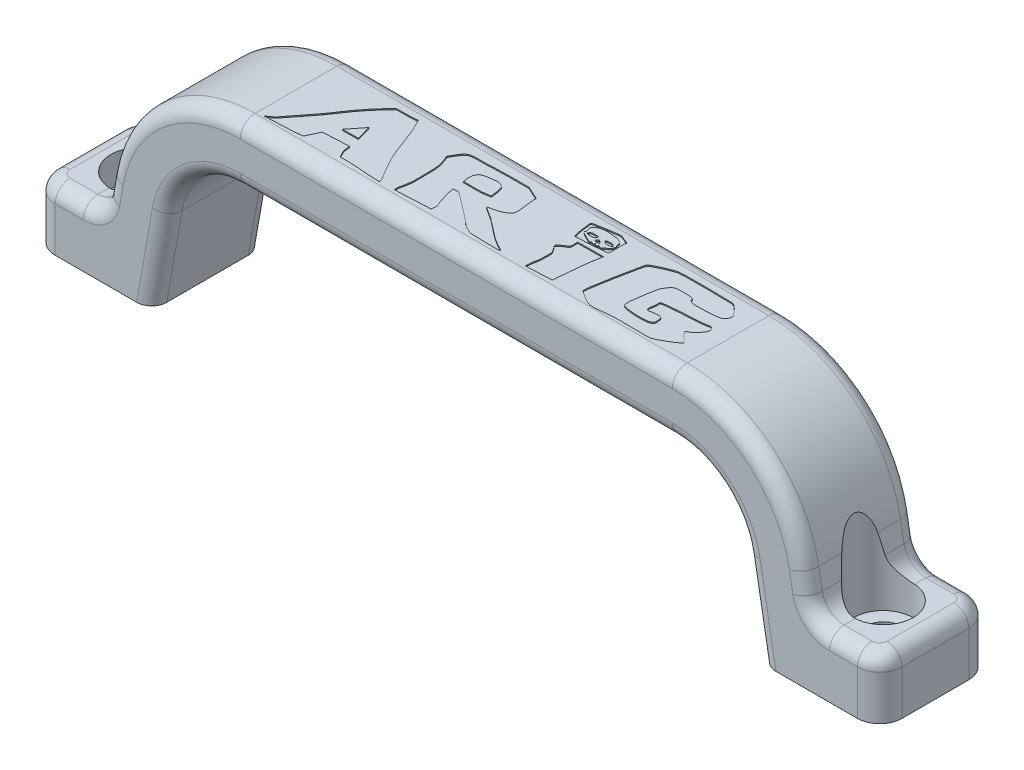
SolidWorks part; units mm, degrees
material "ABS"
ref_plane "Plan de face" through (0, 0, 0) normal (0, 0, 1) x (1, 0, 0)
ref_plane "Plan de dessus" through (0, 0, 0) normal (0, 1, 0) x (1, 0, 0)
ref_plane "Plan de droite" through (0, 0, 0) normal (1, 0, 0) x (0, 0, -1)
sketch "Esquisse1" plane through (0, 0, 0) normal (0, 0, 1) x (1, 0, 0)
  line L0 (-57, 0) -> (-41, 0)
  line L1 (-41, 0) -> (-38.9305, 11.7365)
  line L2 (-29.0825, 20) -> (29.0825, 20)
  line L3 (0, 20) -> (0, 0) construction
  line L4 (41, 0) -> (38.9305, 11.7365)
  line L5 (57, 0) -> (41, 0)
  arc A0 (38.9305, 11.7365) -> (29.0825, 20) centre (29.0825, 10) ccw
  arc A1 (-38.9305, 11.7365) -> (-29.0825, 20) centre (-29.0825, 10) cw
  dimension "D1" = 10
  dimension "D2" = 16
  dimension "D3" = 80
  dimension "D4" = 20
  dimension "D5" = 82
  dimension "D6" = 114
extrude "Extru.-Mince1" add sketch "Esquisse1" along normal mid plane 15 thin thin type one direction wall 8
fillet "Congé1" radius 3 6 edges at (57, 4, -7.5) (57, 4, 7.5) (-57, 4, -7.5) (-57, 4, 7.5) (47.7128, 8, 0) (-47.7128, 8, 0)
fillet "Congé2" radius 2 34 edges at (39.9653, 5.8682, -7.5) (35.5103, 17.6604, -7.5) (0, 20, -7.5) (-35.5103, 17.6604, -7.5) (39.9653, 5.8682, 7.5) (35.5103, 17.6604, 7.5) (0, 20, 7.5) (-35.5103, 17.6604, 7.5) (-56.1213, 8, 6.6213) (-52.115, 8, 7.5) (-48.3017, 8.7019, 7.5) (-47.0423, 11.8024, 7.5) (-40.6526, 23.7888, 7.5) (0, 28, 7.5) (40.6526, 23.7888, 7.5) (47.0423, 11.8024, 7.5) (48.3017, 8.7019, 7.5) (52.115, 8, 7.5) (56.1213, 8, 6.6213) (57, 8, 0) (56.1213, 8, -6.6213) (52.115, 8, -7.5) (48.3017, 8.7019, -7.5) (47.0423, 11.8024, -7.5) (40.6526, 23.7888, -7.5) (0, 28, -7.5) (-40.6526, 23.7888, -7.5) (-47.0423, 11.8024, -7.5) (-48.3017, 8.7019, -7.5) (-52.115, 8, -7.5) (-56.1213, 8, -6.6213) (-39.9653, 5.8682, -7.5) (-39.9653, 5.8682, 7.5) (-57, 8, 0)
hole_wizard "Chambrage pour vis à tête cylindrique à 6 pans creux (ou vis CHC) M41" positions "Esquisse3" profile "Esquisse4" counterbore size "M4" standard "Ansi Metric" end condition through all
sketch "Esquisse3" plane through (0, 8, 0) normal (0, 1, 0) x (1, 0, 0)
  line L0 (0, 0) -> (0, -7.5) construction
  line L1 (29.0825, -7.5) -> (-29.0825, -7.5) construction
  line L3 (-57, -4.5) -> (-57, 4.5) construction
  point P0 (-50, 0)
  point P2 (50, 0)
  dimension "D1" = 7
  dimension "D2" = 100
sketch "Esquisse4" plane through (-50, 8, 0) normal (1, 0, 0) x (0, 0, 1)
  line L0 (0, 0) -> (0, 8)
  line L1 (0, 8) -> (2.15, 8)
  line L2 (0, 0) -> (0, -20)
  line L3 (2.15, 8) -> (2.15, 4)
  line L4 (2.15, 4) -> (4, 4)
  line L5 (4, 4) -> (4, 0)
  line L6 (0, -20) -> (4, -20)
  line L7 (4, 0) -> (0, 0) construction
  line L8 (4, -20) -> (4, 0)
  line L11 (0, -6.35) -> (0, 107.95) construction
  dimension "Diamètre du perçage jusqu'au prochain" = 4.3
  dimension "Profondeur du perçage jusqu'au prochain" = 8
  dimension "Diamètre du chambrage" = 8
  dimension "Profondeur du chambrage" = 4
sketch "Esquisse5" plane through (0, 28, 0) normal (0, 1, 0) x (1, 0, 0)
  line L0 (-29.0825, -5.5) -> (29.0825, -5.5) construction
  line L1 (-29.0825, -5.5) -> (29.0825, -5.5) construction
  line L2 (-18.889, -2.9854) -> (-22.3764, -3.1611)
  line L3 (-20.7574, 3.9425) -> (-20.1614, 4.5686)
  line L4 (-21.3417, -1.4652) -> (-19.2272, -1.4434)
  line L5 (-2.0037, 4.3142) -> (-0.2156, 3.4955)
  line L6 (7.6307, 1.2068) -> (11.0963, 1.2403)
  line L7 (10.3429, -4.9341) -> (6.8672, -5.1049)
  line L8 (8.3288, 2.0373) -> (8.4745, 2.0373)
  line L9 (8.4745, 2.0373) -> (8.5314, 2.1963)
  line L10 (8.5314, 2.1963) -> (8.7457, 2.0322)
  line L11 (8.7457, 2.0322) -> (9.0035, 2.0373)
  line L12 (9.0035, 2.0373) -> (8.9583, 2.2298)
  line L13 (8.9583, 2.2298) -> (9.2396, 2.049)
  line L14 (9.2396, 2.049) -> (9.4539, 2.0607)
  line L15 (9.4539, 2.0607) -> (9.3869, 2.2532)
  line L16 (9.3869, 2.2532) -> (9.7569, 2.0657)
  line L17 (9.7569, 2.0657) -> (9.993, 2.1277)
  line L18 (9.2848, 2.5127) -> (8.8913, 2.4391)
  spline S0 degree 3 poles (-14.4356, -1.9792) (-14.0607, -2.6907) (-13.6011, -3.4612) (-13.0938, -4.2959) (-12.9746, -4.5033) (-12.8804, -4.6792) (-12.8098, -4.8224) (-12.7662, -4.9366) (-12.7443, -5.0296) (-12.7525, -5.0965) (-12.7932, -5.0982) knots 0 0 0 0 0.673145 0.751125 0.817898 0.873508 0.91803 0.951887 0.974709 1 1 1 1
  spline S1 degree 3 poles (-12.7932, -5.0982) (-12.8467, -5.1028) (-12.9417, -5.1016) (-13.0874, -5.1004) (-13.2403, -5.0944) (-13.4227, -5.0879) (-13.6349, -5.0798) (-13.8765, -5.0679) (-14.1387, -5.0526) (-14.4056, -5.0391) (-14.6595, -5.0218) (-14.8927, -5.0052) (-15.1048, -4.9887) (-15.2962, -4.9717) (-15.5098, -4.9518) (-15.6591, -4.9312) (-15.7515, -4.9174) knots 0 0 0 0 0.054223 0.096001 0.147401 0.208975 0.280725 0.362112 0.453705 0.546426 0.632419 0.71109 0.783006 0.847609 0.905466 1 1 1 1
  spline S2 degree 3 poles (-15.7515, -4.9174) (-15.8417, -4.9054) (-15.9856, -4.891) (-16.189, -4.8765) (-16.367, -4.8661) (-16.5629, -4.8595) (-16.7762, -4.8574) (-17.0066, -4.8527) (-17.2455, -4.854) (-17.4771, -4.8539) (-17.6847, -4.853) (-17.8605, -4.8559) (-18.0045, -4.8553) (-18.1166, -4.8554) (-18.202, -4.8554) (-18.25, -4.8554) (-18.2712, -4.8554) knots 0 0 0 0 0.108138 0.172034 0.242512 0.320224 0.405204 0.496157 0.594402 0.689329 0.771642 0.841347 0.898435 0.942911 0.974775 1 1 1 1
  spline S3 degree 3 poles (-18.2712, -4.8554) (-18.278, -4.8446) (-18.2906, -4.8196) (-18.3144, -4.776) (-18.3465, -4.7195) (-18.3862, -4.6453) (-18.4365, -4.5558) (-18.4953, -4.4499) (-18.5821, -4.2927) (-18.6816, -4.0971) (-18.7917, -3.8172) (-18.8281, -3.6105) (-18.822, -3.4826) knots 0 0 0 0 0.025534 0.05606 0.09962 0.155674 0.224762 0.305364 0.39846 0.58452 0.744873 1 1 1 1
  spline S4 degree 3 poles (-18.822, -3.4826) (-18.821, -3.4173) (-18.8438, -3.2512) (-18.867, -3.0856) (-18.889, -2.9854) knots 0 0 0 0 0.388377 1 1 1 1
  spline S5 degree 3 poles (-22.3764, -3.1611) (-22.5656, -3.5495) (-22.776, -3.9803) (-22.9897, -4.455) (-23.042, -4.5667) (-23.085, -4.6618) (-23.1209, -4.7399) (-23.148, -4.8005) (-23.1708, -4.8461) (-23.182, -4.872) (-23.1867, -4.8839) knots 0 0 0 0 0.680866 0.755243 0.82016 0.875251 0.919717 0.955522 0.979907 1 1 1 1
  spline S6 degree 3 poles (-23.1867, -4.8839) (-23.1989, -4.8862) (-23.2275, -4.8891) (-23.2777, -4.8963) (-23.3439, -4.9071) (-23.4284, -4.9177) (-23.532, -4.9341) (-23.6545, -4.9494) (-23.8404, -4.9773) (-24.0796, -5.0077) (-24.4485, -5.0391) (-24.7194, -5.0547) (-24.896, -5.053) knots 0 0 0 0 0.021624 0.050129 0.088552 0.138678 0.198718 0.271429 0.354053 0.526763 0.691971 1 1 1 1
  spline S7 degree 3 poles (-24.896, -5.053) (-24.9993, -5.0541) (-25.1684, -5.0559) (-25.4128, -5.0652) (-25.6389, -5.0728) (-25.8927, -5.0854) (-26.1752, -5.0982) (-26.4854, -5.1155) (-26.8124, -5.1332) (-27.1311, -5.1506) (-27.4179, -5.1679) (-27.6601, -5.1813) (-27.8583, -5.1912) (-28.0123, -5.199) (-28.13, -5.2073) (-28.1965, -5.2094) (-28.226, -5.212) knots 0 0 0 0 0.092911 0.1522 0.220037 0.296445 0.380903 0.474438 0.576024 0.675603 0.761618 0.834541 0.893872 0.940138 0.973341 1 1 1 1
  spline S8 degree 3 poles (-28.226, -5.212) (-28.0841, -5.1262) (-27.8808, -4.994) (-27.6252, -4.8095) (-27.4569, -4.6719) (-27.3027, -4.5361) (-27.1664, -4.3992) (-27.0437, -4.2633) (-26.9037, -4.0765) (-26.7341, -3.8369) (-26.4359, -3.4415) (-26.1971, -3.1458) (-26.0328, -2.9452) knots 0 0 0 0 0.15625 0.228518 0.296937 0.361009 0.421997 0.478993 0.533376 0.641835 0.755643 1 1 1 1
  spline S9 degree 3 poles (-26.0328, -2.9452) (-25.5761, -2.391) (-24.9116, -1.542) (-24.0739, -0.373) (-23.5732, 0.3753) (-23.176, 0.9776) (-22.8612, 1.4197) (-22.5367, 1.8556) (-22.2038, 2.2871) (-21.858, 2.7107) (-21.383, 3.2693) (-21.0099, 3.6751) (-20.7574, 3.9425) knots 0 0 0 0 0.248041 0.37225 0.496661 0.559052 0.621415 0.684102 0.746758 0.809649 0.872959 1 1 1 1
  spline S10 degree 3 poles (-20.1614, 4.5686) (-19.9555, 4.5668) (-19.6217, 4.5718) (-19.1435, 4.5753) (-18.7266, 4.5794) (-18.3085, 4.5892) (-17.8262, 4.6059) (-17.4892, 4.6336) (-17.2818, 4.659) knots 0 0 0 0 0.214328 0.347341 0.497783 0.648255 0.782526 1 1 1 1
  spline S11 degree 3 poles (-17.2818, 4.659) (-17.1349, 4.3931) (-16.9187, 3.9859) (-16.6528, 3.4236) (-16.453, 2.9845) (-16.2613, 2.5301) (-16.0728, 2.0629) (-15.8931, 1.5804) (-15.7186, 1.0912) (-15.5501, 0.609) (-15.381, 0.1508) (-15.2161, -0.2776) (-15.0528, -0.6758) (-14.8946, -1.0443) (-14.6979, -1.4801) (-14.54, -1.7856) (-14.4356, -1.9792) knots 0 0 0 0 0.12604 0.191178 0.258011 0.326169 0.395773 0.466985 0.539777 0.611245 0.678854 0.742401 0.801689 0.857382 0.908772 1 1 1 1
  spline S12 degree 3 poles (-19.2272, -1.4434) (-19.3218, -1.0711) (-19.4416, -0.6139) (-19.5962, -0.0857) (-19.6762, 0.1947) (-19.7385, 0.3881) (-19.778, 0.507) knots 0 0 0 0 0.568584 0.699277 0.814541 1 1 1 1
  spline S13 degree 3 poles (-19.778, 0.507) (-19.938, 0.3091) (-20.169, 0.019) (-20.4678, -0.3557) (-20.671, -0.6102) (-20.8583, -0.8486) (-21.0816, -1.1306) (-21.2392, -1.3359) (-21.3417, -1.4652) knots 0 0 0 0 0.303339 0.442024 0.571255 0.691554 0.803336 1 1 1 1
  spline S14 degree 3 poles (-10.5304, -2.5668) (-10.5429, -2.1383) (-10.5519, -1.5093) (-10.5646, -0.6884) (-10.5599, -0.2011) (-10.5708, 0.1845) (-10.5994, 0.4787) (-10.6495, 0.7813) (-10.7151, 1.0927) (-10.8063, 1.4107) (-10.9487, 1.8565) (-11.0842, 2.1883) (-11.1833, 2.4106) knots 0 0 0 0 0.253586 0.372109 0.485673 0.541829 0.600202 0.66039 0.723198 0.788316 0.855967 1 1 1 1
  spline S15 degree 3 poles (-11.1833, 2.4106) (-11.1744, 2.4262) (-11.1548, 2.4611) (-11.1179, 2.5224) (-11.0724, 2.6041) (-11.0109, 2.7074) (-10.9404, 2.8356) (-10.8514, 2.9842) (-10.7567, 3.1527) (-10.6526, 3.3222) (-10.55, 3.4824) (-10.4461, 3.623) (-10.3437, 3.7459) (-10.2438, 3.8519) (-10.1179, 3.9647) (-10.0149, 4.0284) (-9.9461, 4.0614) knots 0 0 0 0 0.025828 0.05742 0.102619 0.160038 0.229973 0.312526 0.408687 0.50717 0.598024 0.68164 0.75783 0.827507 0.890493 1 1 1 1
  spline S16 degree 3 poles (-9.9461, 4.0614) (-9.8736, 4.0937) (-9.7506, 4.1287) (-9.5719, 4.1646) (-9.4091, 4.1857) (-9.2269, 4.1998) (-9.0248, 4.2104) (-8.8032, 4.2128) (-8.5671, 4.2106) (-8.3283, 4.2068) (-8.0983, 4.2047) (-7.8829, 4.2064) (-7.6825, 4.211) (-7.4961, 4.2201) (-7.277, 4.2316) (-7.1204, 4.2479) (-7.0213, 4.2589) knots 0 0 0 0 0.080682 0.129987 0.185653 0.247863 0.316204 0.391862 0.473771 0.556823 0.635318 0.708126 0.776403 0.839604 0.898289 1 1 1 1
  spline S17 degree 3 poles (-7.0213, 4.2589) (-6.9649, 4.2638) (-6.8719, 4.2726) (-6.736, 4.277) (-6.6089, 4.285) (-6.4643, 4.2897) (-6.303, 4.2919) (-6.1245, 4.2983) (-5.7237, 4.3034) (-5.0965, 4.3148) (-4.3928, 4.3166) (-3.8319, 4.3197) (-3.4307, 4.3188) (-3.0528, 4.3201) (-2.7548, 4.3168) (-2.5366, 4.3182) (-2.3971, 4.3154) (-2.2788, 4.3156) (-2.1822, 4.3167) (-2.1075, 4.3137) (-2.0506, 4.3143) (-2.0182, 4.3142) (-2.0037, 4.3142) knots 0 0 0 0 0.033799 0.055838 0.081226 0.109932 0.142297 0.177672 0.216707 0.38185 0.55265 0.637383 0.71711 0.792501 0.863223 0.895247 0.922937 0.946622 0.96597 0.980652 0.991327 1 1 1 1
  spline S18 degree 3 poles (-0.2156, 3.4955) (-0.2426, 3.4104) (-0.2537, 3.2607) (-0.2422, 3.0401) (-0.205, 2.7504) (-0.1438, 2.3542) (-0.0788, 1.8604) (-0.0213, 1.3648) (0.0044, 0.9639) (0.0063, 0.67) (-0.0179, 0.4419) (-0.0702, 0.2915) (-0.1252, 0.2124) knots 0 0 0 0 0.079959 0.134413 0.199323 0.343349 0.496285 0.648797 0.793602 0.858577 0.913866 1 1 1 1
  spline S19 degree 3 poles (-0.1252, 0.2124) (-0.1725, 0.1478) (-0.2565, 0.0559) (-0.3886, -0.0517) (-0.5046, -0.1302) (-0.6307, -0.2096) (-0.7728, -0.283) (-0.9279, -0.3526) (-1.1537, -0.4422) (-1.4534, -0.5454) (-1.9646, -0.6948) (-2.3619, -0.7833) (-2.6332, -0.8323) knots 0 0 0 0 0.086644 0.134368 0.184384 0.238453 0.29583 0.357574 0.422742 0.559179 0.701057 1 1 1 1
  spline S20 degree 3 poles (-2.6332, -0.8323) (-2.3557, -0.9911) (-1.9469, -1.2363) (-1.4165, -1.5794) (-1.0332, -1.8429) (-0.6597, -2.1108) (-0.2961, -2.3833) (0.0563, -2.6629) (0.3962, -2.9518) (0.7381, -3.2383) (1.0938, -3.5123) (1.4615, -3.7785) (1.8423, -4.0344) (2.2345, -4.2828) (2.778, -4.604) (3.1996, -4.827) (3.486, -4.9693) knots 0 0 0 0 0.129563 0.193176 0.255975 0.318051 0.379436 0.440121 0.500327 0.560243 0.620865 0.682259 0.744175 0.806797 0.870374 1 1 1 1
  spline S21 degree 3 poles (3.486, -4.9693) (3.4288, -4.9938) (3.3253, -5.0197) (3.1677, -5.0382) (3.0096, -5.0491) (2.8243, -5.0582) (2.6115, -5.058) (2.3715, -5.0577) (2.1059, -5.0475) (1.818, -5.0378) (1.5122, -5.0272) (1.1896, -5.0194) (0.8508, -5.0109) (0.4948, -5.0025) (-0.0125, -4.9913) (-0.4014, -4.9825) (-0.666, -4.9793) knots 0 0 0 0 0.04478 0.076413 0.11433 0.159027 0.210115 0.26764 0.332033 0.401666 0.47532 0.55258 0.634264 0.719567 0.809293 1 1 1 1
  spline S22 degree 3 poles (-0.666, -4.9793) (-0.6779, -4.9729) (-0.7065, -4.9616) (-0.7561, -4.9373) (-0.8225, -4.9084) (-0.9072, -4.8691) (-1.0099, -4.8204) (-1.133, -4.766) (-1.2684, -4.7024) (-1.4073, -4.6375) (-1.5366, -4.5701) (-1.6524, -4.5051) (-1.7547, -4.4415) (-1.8437, -4.3803) (-1.937, -4.3041) (-1.9963, -4.2436) (-2.0271, -4.2008) knots 0 0 0 0 0.025606 0.058307 0.104771 0.16307 0.235576 0.320438 0.418541 0.519463 0.611378 0.695336 0.771465 0.839935 0.900157 1 1 1 1
  spline S23 degree 3 poles (-2.0271, -4.2008) (-2.0459, -4.179) (-2.0794, -4.1408) (-2.1384, -4.0905) (-2.1984, -4.0367) (-2.2696, -3.9726) (-2.3564, -3.9028) (-2.4542, -3.8226) (-2.6053, -3.7019) (-2.8101, -3.537) (-3.0754, -3.3298) (-3.3615, -3.107) (-3.7763, -2.7872) (-4.3218, -2.3693) (-4.8814, -1.9532) (-5.3269, -1.6216) (-5.7293, -1.3173) (-6.025, -1.104) (-6.2109, -0.9629) knots 0 0 0 0 0.016345 0.028666 0.043902 0.062053 0.082952 0.107011 0.133786 0.192524 0.256056 0.324581 0.3981 0.552912 0.714045 0.793378 0.867713 1 1 1 1
  spline S24 degree 2 poles (-6.2109, -0.9629) (-6.5938, -0.972) (-6.9761, -0.9964) knots 0 0 0 1 1 1
  spline S25 degree 3 poles (-6.9761, -0.9964) (-6.9237, -1.2417) (-6.8374, -1.6264) (-6.6934, -2.1572) (-6.5937, -2.5196) (-6.5083, -2.8095) (-6.4464, -3.008) (-6.3896, -3.1839) (-6.3378, -3.337) (-6.2901, -3.4675) (-6.2358, -3.5959) (-6.1954, -3.6798) (-6.1657, -3.7253) knots 0 0 0 0 0.263802 0.414408 0.578294 0.65907 0.732204 0.796974 0.853392 0.902229 0.942993 1 1 1 1
  spline S26 degree 3 poles (-6.1657, -3.7253) (-6.1048, -3.8143) (-6.0505, -3.9738) (-6.026, -4.205) (-6.0382, -4.3619) (-6.051, -4.4866) (-6.0622, -4.5696) (-6.0679, -4.6407) (-6.0747, -4.6986) (-6.0805, -4.7437) (-6.0821, -4.7781) (-6.0878, -4.7967) (-6.0871, -4.8052) knots 0 0 0 0 0.288847 0.450005 0.627169 0.713843 0.789997 0.853798 0.907071 0.948153 0.977044 1 1 1 1
  spline S27 degree 3 poles (-6.0871, -4.8052) (-6.0999, -4.8053) (-6.1295, -4.8048) (-6.1819, -4.8074) (-6.2511, -4.8087) (-6.3393, -4.8104) (-6.4476, -4.8121) (-6.5754, -4.8133) (-6.7685, -4.8183) (-7.0118, -4.8245) (-7.369, -4.8379) (-7.6244, -4.8606) (-7.7864, -4.8789) knots 0 0 0 0 0.022629 0.052162 0.092512 0.144667 0.207642 0.283407 0.37001 0.548159 0.71261 1 1 1 1
  spline S28 degree 3 poles (-7.7864, -4.8789) (-7.8772, -4.8894) (-8.0245, -4.9032) (-8.2356, -4.9199) (-8.4264, -4.933) (-8.639, -4.9471) (-8.8735, -4.9573) (-9.1295, -4.9723) (-9.3987, -4.982) (-9.6636, -4.9949) (-9.9071, -5.0017) (-10.1207, -5.0115) (-10.3049, -5.016) (-10.4595, -5.0195) (-10.6063, -5.0216) (-10.7012, -5.0217) (-10.7547, -5.0195) knots 0 0 0 0 0.092245 0.149306 0.213668 0.285335 0.364281 0.450568 0.544141 0.636026 0.718301 0.789882 0.851857 0.904246 0.945926 1 1 1 1
  spline S29 degree 3 poles (-10.7547, -5.0195) (-10.7937, -5.0185) (-10.8336, -4.9655) (-10.8522, -4.871) (-10.8554, -4.7632) (-10.8453, -4.6257) (-10.8252, -4.4585) (-10.7906, -4.2615) (-10.7445, -4.0427) (-10.6946, -3.8156) (-10.6512, -3.5946) (-10.6145, -3.388) (-10.5838, -3.1961) (-10.5602, -3.0186) (-10.5388, -2.8106) (-10.5305, -2.6613) (-10.5304, -2.5668) knots 0 0 0 0 0.04096 0.071715 0.114252 0.168794 0.235661 0.314465 0.406651 0.501708 0.591028 0.674639 0.751262 0.822248 0.887649 1 1 1 1
  spline S30 degree 3 poles (-4.7594, 2.8794) (-4.7813, 2.8776) (-4.8307, 2.8695) (-4.919, 2.8599) (-5.0352, 2.8464) (-5.1835, 2.8277) (-5.3654, 2.8058) (-5.5804, 2.7812) (-5.819, 2.7526) (-6.0612, 2.7197) (-6.2863, 2.6716) (-6.4841, 2.6119) (-6.6568, 2.5419) (-6.8019, 2.4589) (-6.9587, 2.3397) (-7.0413, 2.2227) (-7.0765, 2.1394) knots 0 0 0 0 0.026058 0.059427 0.105455 0.164877 0.236958 0.323013 0.421805 0.522263 0.613111 0.694859 0.767341 0.833832 0.892821 1 1 1 1
  spline S31 degree 3 poles (-7.0765, 2.1394) (-7.1434, 1.9803) (-7.209, 1.7282) (-7.2249, 1.3828) (-7.2045, 1.1695) (-7.1757, 1.0083) (-7.1598, 0.902) (-7.144, 0.8124) (-7.133, 0.7385) (-7.1228, 0.6817) (-7.1147, 0.6383) (-7.1126, 0.6135) (-7.11, 0.6025) knots 0 0 0 0 0.330717 0.494743 0.661416 0.740644 0.808958 0.867587 0.915301 0.952276 0.978333 1 1 1 1
  spline S32 degree 3 poles (-7.11, 0.6025) (-7.0882, 0.6028) (-7.0397, 0.6001) (-6.9532, 0.599) (-6.8393, 0.5975) (-6.6931, 0.5936) (-6.5145, 0.5904) (-6.3036, 0.5876) (-6.0687, 0.5818) (-5.8276, 0.5789) (-5.5982, 0.5772) (-5.3889, 0.5765) (-5.2003, 0.5802) (-5.0328, 0.5852) (-4.8506, 0.5926) (-4.7246, 0.6045) (-4.6472, 0.6142) knots 0 0 0 0 0.026508 0.059125 0.105328 0.16513 0.237157 0.322771 0.421982 0.523219 0.616298 0.701221 0.778003 0.845972 0.905141 1 1 1 1
  spline S33 degree 3 poles (-4.6472, 0.6142) (-4.4019, 0.6491) (-4.1035, 0.6834) (-3.7702, 0.7367) (-3.6515, 0.7516) (-3.5852, 0.762) (-3.5557, 0.7665) knots 0 0 0 0 0.674543 0.8174 0.918582 1 1 1 1
  spline S34 degree 3 poles (-3.5557, 0.7665) (-3.5581, 0.7793) (-3.5606, 0.8085) (-3.5686, 0.8596) (-3.5766, 0.9272) (-3.5864, 1.0144) (-3.5998, 1.121) (-3.6171, 1.2464) (-3.6404, 1.4372) (-3.677, 1.6816) (-3.7471, 2.0556) (-3.825, 2.3238) (-3.8821, 2.496) knots 0 0 0 0 0.022024 0.049814 0.088082 0.137774 0.199002 0.27083 0.353135 0.525922 0.691249 1 1 1 1
  spline S35 degree 3 poles (-3.8821, 2.496) (-3.9413, 2.5681) (-4.0606, 2.6524) (-4.2439, 2.7401) (-4.4017, 2.7844) (-4.5453, 2.8245) (-4.6638, 2.8529) (-4.7295, 2.8731) (-4.7594, 2.8794) knots 0 0 0 0 0.284229 0.445866 0.624362 0.788398 0.905665 1 1 1 1
  spline S36 degree 3 poles (11.0963, 1.2403) (11.0949, 1.2249) (11.0838, 1.1911) (11.0738, 1.1291) (11.0561, 1.0489) (11.0337, 0.9459) (11.0102, 0.8192) (10.9767, 0.6703) (10.9441, 0.5035) (10.9077, 0.3331) (10.8755, 0.1697) (10.8492, 0.0193) (10.8256, -0.1179) (10.8056, -0.2418) (10.7838, -0.3804) (10.7735, -0.4783) (10.7698, -0.5393) knots 0 0 0 0 0.025603 0.058611 0.103952 0.161629 0.233267 0.317425 0.414634 0.514748 0.606154 0.690687 0.767614 0.83694 0.898671 1 1 1 1
  spline S37 degree 3 poles (10.7698, -0.5393) (10.7635, -0.5765) (10.7583, -0.6421) (10.7452, -0.7401) (10.7359, -0.8402) (10.7241, -0.9562) (10.7104, -1.0901) (10.6957, -1.2408) (10.6604, -1.5895) (10.6102, -2.1427) (10.5501, -2.7676) (10.5043, -3.2711) (10.4711, -3.6345) (10.4371, -3.9776) (10.4114, -4.2495) (10.3897, -4.4485) (10.3795, -4.576) (10.3666, -4.6829) (10.3584, -4.7706) (10.3524, -4.8393) (10.3454, -4.8916) (10.3457, -4.9215) (10.3429, -4.9341) knots 0 0 0 0 0.025587 0.044681 0.067166 0.09384 0.123946 0.158618 0.196722 0.362009 0.536048 0.623239 0.705487 0.78396 0.857491 0.891031 0.919969 0.944379 0.964186 0.979805 0.991237 1 1 1 1
  spline S38 degree 3 poles (6.8672, -5.1049) (6.8666, -5.0925) (6.872, -5.0654) (6.8737, -5.0167) (6.8801, -4.9532) (6.8835, -4.8709) (6.8935, -4.7707) (6.9009, -4.6517) (6.9137, -4.4769) (6.9327, -4.2695) (6.9646, -4.0135) (6.9994, -3.8482) (7.0347, -3.7588) knots 0 0 0 0 0.027228 0.060557 0.107483 0.167917 0.242037 0.329658 0.430874 0.628707 0.788886 1 1 1 1
  spline S39 degree 3 poles (7.0347, -3.7588) (7.0497, -3.7194) (7.0663, -3.6496) (7.0789, -3.5435) (7.0912, -3.4387) (7.1007, -3.3164) (7.1091, -3.1768) (7.1156, -3.0194) (7.1204, -2.8498) (7.1231, -2.6795) (7.1266, -2.5205) (7.1298, -2.3782) (7.1335, -2.2526) (7.1357, -2.1438) (7.1341, -2.0322) (7.138, -1.9569) (7.1368, -1.9122) knots 0 0 0 0 0.068225 0.115622 0.172882 0.239047 0.314159 0.399149 0.494037 0.588904 0.674739 0.751544 0.819317 0.878041 0.927724 1 1 1 1
  spline S40 degree 3 poles (7.1368, -1.9122) (7.1345, -1.8287) (7.0927, -1.6941) (6.9959, -1.5115) (6.8942, -1.3483) (6.7867, -1.1856) (6.6576, -1.0092) (6.5687, -0.8881) (6.5073, -0.8206) knots 0 0 0 0 0.194516 0.327213 0.485728 0.64667 0.785859 1 1 1 1
  spline S41 degree 3 poles (6.5073, -0.8206) (6.4847, -0.7961) (6.4692, -0.7443) (6.4841, -0.6723) (6.5144, -0.6137) (6.5611, -0.5508) (6.6264, -0.4842) (6.7076, -0.411) (6.837, -0.3126) (6.9971, -0.1975) (7.2144, -0.0491) (7.3669, 0.0452) (7.4633, 0.0935) knots 0 0 0 0 0.069173 0.107801 0.153967 0.208312 0.273773 0.351909 0.440673 0.61915 0.771185 1 1 1 1
  spline S42 degree 3 poles (7.4633, 0.0935) (7.4994, 0.1144) (7.5533, 0.1547) (7.5985, 0.2345) (7.626, 0.3064) (7.6488, 0.3892) (7.6587, 0.4845) (7.6643, 0.5913) (7.6597, 0.7058) (7.6523, 0.8184) (7.6479, 0.92) (7.6429, 1.006) (7.6377, 1.0762) (7.6338, 1.1309) (7.6331, 1.1728) (7.6303, 1.1962) (7.6307, 1.2068) knots 0 0 0 0 0.107362 0.165306 0.230947 0.302915 0.383033 0.473988 0.574822 0.674357 0.761059 0.833585 0.893361 0.940294 0.972977 1 1 1 1
  spline S43 degree 3 poles (9.859, 4.3041) (9.8446, 4.3065) (9.811, 4.3092) (9.7519, 4.3169) (9.6738, 4.3251) (9.5743, 4.3346) (9.4522, 4.3486) (9.3083, 4.3652) (9.0903, 4.3898) (8.8143, 4.4156) (8.4011, 4.4303) (8.1023, 4.4205) (7.9119, 4.3945) knots 0 0 0 0 0.022426 0.051756 0.091397 0.143057 0.205122 0.280148 0.365486 0.541792 0.705537 1 1 1 1
  spline S44 degree 3 poles (7.9119, 4.3945) (7.7473, 4.373) (7.5092, 4.3175) (7.2307, 4.1708) (7.0888, 4.0576) (6.9938, 3.961) (6.9325, 3.8954) (6.8828, 3.8357) (6.8423, 3.7819) (6.8162, 3.7316) (6.7933, 3.6779) (6.7913, 3.6372) (6.7986, 3.6143) knots 0 0 0 0 0.344723 0.499299 0.64819 0.718463 0.779796 0.833948 0.879488 0.918777 0.950968 1 1 1 1
  spline S45 degree 3 poles (6.7986, 3.6143) (6.8104, 3.5624) (6.8356, 3.4799) (6.8677, 3.3606) (6.8995, 3.2591) (6.9262, 3.1576) (6.9362, 3.0388) (6.9175, 2.9562) (6.889, 2.9129) knots 0 0 0 0 0.219895 0.356435 0.510406 0.659764 0.789246 1 1 1 1
  spline S46 degree 3 poles (6.889, 2.9129) (6.8736, 2.8943) (6.8668, 2.8547) (6.889, 2.8053) (6.9207, 2.7666) (6.9676, 2.7263) (7.0292, 2.6839) (7.1056, 2.6386) (7.222, 2.5765) (7.3662, 2.5078) (7.5541, 2.416) (7.6797, 2.3524) (7.7546, 2.3152) knots 0 0 0 0 0.063204 0.098954 0.14288 0.197212 0.265226 0.344154 0.436341 0.620641 0.774675 1 1 1 1
  spline S47 degree 3 poles (7.7546, 2.3152) (7.8777, 2.2529) (8.0307, 2.1769) (8.2068, 2.0951) (8.2738, 2.0622) (8.3124, 2.0458) (8.3288, 2.0373) knots 0 0 0 0 0.649002 0.802776 0.913114 1 1 1 1
  spline S48 degree 3 poles (9.993, 2.1277) (10.0096, 2.1446) (10.0562, 2.1883) (10.097, 2.2396) (10.1068, 2.28) knots 0 0 0 0 0.369097 1 1 1 1
  spline S49 degree 3 poles (10.1068, 2.28) (10.1086, 2.3071) (10.1456, 2.3374) (10.205, 2.3789) (10.2761, 2.411) (10.3491, 2.4466) (10.4294, 2.4895) (10.4819, 2.5222) (10.5103, 2.5462) knots 0 0 0 0 0.150435 0.277872 0.445302 0.623392 0.774147 1 1 1 1
  spline S50 degree 3 poles (10.5103, 2.5462) (10.54, 2.5787) (10.5853, 2.643) (10.6473, 2.7483) (10.709, 2.8541) (10.7669, 2.9656) (10.8105, 3.099) (10.8137, 3.1973) (10.7916, 3.2527) knots 0 0 0 0 0.167592 0.299474 0.466459 0.63508 0.777913 1 1 1 1
  spline S51 degree 3 poles (10.7916, 3.2527) (10.7511, 3.3482) (10.6778, 3.5119) (10.6283, 3.6855) (10.6241, 3.7617) knots 0 0 0 0 0.57778 1 1 1 1
  spline S52 degree 3 poles (10.6241, 3.7617) (10.6267, 3.8146) (10.578, 3.9369) (10.4676, 4.0076) (10.4098, 4.0496) knots 0 0 0 0 0.415543 1 1 1 1
  spline S53 degree 3 poles (10.4098, 4.0496) (10.3652, 4.0773) (10.2887, 4.1149) (10.1779, 4.1681) (10.0808, 4.2086) (9.9925, 4.2492) (9.9183, 4.2779) (9.878, 4.2976) (9.859, 4.3041) knots 0 0 0 0 0.259108 0.420684 0.607139 0.778754 0.901134 1 1 1 1
  spline S54 degree 3 poles (10.1738, 3.3381) (10.1872, 3.3319) (10.2152, 3.3144) (10.2655, 3.2843) (10.3261, 3.2465) (10.3918, 3.2068) (10.464, 3.1583) (10.5088, 3.1191) (10.5337, 3.0937) knots 0 0 0 0 0.101408 0.227084 0.402776 0.592293 0.755113 1 1 1 1
  spline S55 degree 3 poles (10.5337, 3.0937) (10.5519, 3.0654) (10.5131, 3.0224) (10.4379, 2.9859) (10.2313, 2.9151) (10.0391, 2.8892) (9.8808, 2.8961) knots 0 0 0 0 0.106872 0.206716 0.350735 1 1 1 1
  spline S56 degree 3 poles (9.8808, 2.8961) (9.8028, 2.8958) (9.6921, 2.9146) (9.5563, 2.9637) (9.4773, 3.0152) (9.4182, 3.0714) (9.3736, 3.1476) (9.3819, 3.2126) (9.4087, 3.241) knots 0 0 0 0 0.337587 0.485996 0.624791 0.745022 0.838468 1 1 1 1
  spline S57 degree 3 poles (9.4087, 3.241) (9.4417, 3.2864) (9.534, 3.3182) (9.6785, 3.3386) (9.8228, 3.3398) (9.9623, 3.3406) (10.0789, 3.3376) (10.1448, 3.3382) (10.1738, 3.3381) knots 0 0 0 0 0.202077 0.358792 0.556316 0.749492 0.889614 1 1 1 1
  spline S58 degree 3 poles (8.8579, 2.8744) (8.8835, 2.8756) (8.9239, 2.8601) (8.9815, 2.8296) (9.0738, 2.7614) (9.1516, 2.7041) (9.2061, 2.6534) knots 0 0 0 0 0.179059 0.306198 0.467195 1 1 1 1
  spline S59 degree 3 poles (9.2061, 2.6534) (9.2353, 2.6271) (9.2597, 2.5783) (9.2809, 2.5284) (9.2848, 2.5127) knots 0 0 0 0 0.703305 1 1 1 1
  spline S60 degree 3 poles (8.8913, 2.4391) (8.8612, 2.4484) (8.7751, 2.4735) (8.6926, 2.5099) (8.6436, 2.5412) knots 0 0 0 0 0.352544 1 1 1 1
  spline S61 degree 3 poles (8.6436, 2.5412) (8.6149, 2.5497) (8.6053, 2.5989) (8.6363, 2.6613) (8.6769, 2.7206) (8.7261, 2.7795) (8.7843, 2.8352) (8.8264, 2.8693) (8.8579, 2.8744) knots 0 0 0 0 0.16527 0.285685 0.460366 0.645507 0.795737 1 1 1 1
  spline S62 degree 3 poles (8.441, 3.2192) (8.4358, 3.1966) (8.4265, 3.0987) (8.3797, 3.0086) (8.3506, 2.9413) knots 0 0 0 0 0.23719 1 1 1 1
  spline S63 degree 3 poles (8.3506, 2.9413) (8.3217, 2.8841) (8.2264, 2.8307) (8.0704, 2.7971) (7.9149, 2.7878) (7.754, 2.7844) (7.5722, 2.7888) (7.4473, 2.7972) (7.3728, 2.8124) knots 0 0 0 0 0.178437 0.30618 0.466999 0.63386 0.777827 1 1 1 1
  spline S64 degree 3 poles (7.3728, 2.8124) (7.333, 2.8203) (7.2488, 2.8396) (7.2277, 2.9339) (7.2539, 3.0002) (7.2959, 3.0659) (7.3683, 3.1532) (7.4453, 3.1948) (7.4967, 3.2192) knots 0 0 0 0 0.235848 0.327074 0.442573 0.579189 0.714482 1 1 1 1
  spline S65 degree 3 poles (7.4967, 3.2192) (7.5658, 3.2457) (7.6899, 3.2642) (7.8752, 3.2641) (8.0444, 3.2542) (8.2032, 3.2384) (8.3345, 3.229) (8.408, 3.221) (8.441, 3.2192) knots 0 0 0 0 0.232106 0.392378 0.584632 0.766719 0.895715 1 1 1 1
  spline S66 degree 3 poles (11.118, 4.3945) (11.1258, 4.3884) (11.1026, 4.3618) (11.0953, 4.3191) (11.0218, 4.1708) (11.007, 4.0289) (11.0059, 3.9073) knots 0 0 0 0 0.053979 0.14634 0.286106 1 1 1 1
  spline S67 degree 3 poles (11.0059, 3.9073) (11.005, 3.8604) (11.0077, 3.7807) (11.009, 3.6607) (11.0126, 3.5412) (11.018, 3.4023) (11.023, 3.2438) (11.0274, 3.0657) (11.0345, 2.8749) (11.0404, 2.6863) (11.0392, 2.5143) (11.031, 2.3662) (11.018, 2.2422) (11.0013, 2.1406) (10.9719, 2.0483) (10.9404, 1.9909) (10.9054, 1.9753) knots 0 0 0 0 0.071573 0.121845 0.183209 0.253967 0.334091 0.425286 0.525874 0.625585 0.71334 0.788432 0.851844 0.903813 0.945034 1 1 1 1
  spline S68 degree 3 poles (10.9054, 1.9753) (10.8801, 1.9678) (10.8336, 1.9561) (10.7602, 1.9483) (10.6817, 1.9375) (10.5875, 1.9254) (10.4762, 1.9166) (10.3497, 1.9041) (10.1571, 1.8888) (9.8998, 1.8695) (9.5779, 1.8453) (9.2418, 1.8248) (8.7832, 1.793) (8.2223, 1.7587) (7.7295, 1.7282) (7.423, 1.7114) (7.2931, 1.7026) (7.1787, 1.6957) (7.0804, 1.6912) (6.9983, 1.6864) (6.9214, 1.6799) (6.8717, 1.6768) (6.8438, 1.6756) knots 0 0 0 0 0.019443 0.035193 0.054255 0.077854 0.105086 0.136448 0.171494 0.247321 0.326427 0.409194 0.495268 0.664903 0.822978 0.858787 0.890905 0.918895 0.943171 0.963343 0.979416 1 1 1 1
  spline S69 degree 3 poles (6.8438, 1.6756) (6.7921, 1.6781) (6.7416, 1.7576) (6.6834, 1.8866) (6.6184, 2.1116) (6.5412, 2.441) (6.4644, 2.8682) (6.3997, 3.3039) (6.3555, 3.6552) (6.331, 3.9056) (6.3158, 4.0685) (6.3068, 4.1701) (6.3047, 4.2238) knots 0 0 0 0 0.051827 0.099088 0.162693 0.315468 0.483292 0.654026 0.814592 0.884502 0.939123 1 1 1 1
  spline S70 degree 3 poles (6.3047, 4.2238) (6.3097, 4.2541) (6.3475, 4.2907) (6.4141, 4.3296) (6.4891, 4.3612) (6.5836, 4.3903) (6.6974, 4.4206) (6.831, 4.4484) (7.3552, 4.5371) (7.8347, 4.6151) (8.2618, 4.6942) knots 0 0 0 0 0.042498 0.074128 0.113412 0.161627 0.219285 0.286324 0.362059 1 1 1 1
  spline S71 degree 3 poles (8.2618, 4.6942) (8.457, 4.7321) (8.7348, 4.7758) (9.0824, 4.8326) (9.294, 4.8609) (9.4732, 4.8816) (9.6467, 4.8958) (9.761, 4.8993) (9.8255, 4.8918) knots 0 0 0 0 0.37758 0.534295 0.669105 0.78327 0.876873 1 1 1 1
  spline S72 degree 3 poles (9.8255, 4.8918) (9.8653, 4.8847) (9.9298, 4.8667) (10.0216, 4.8353) (10.1081, 4.8056) (10.204, 4.7663) (10.312, 4.723) (10.4304, 4.673) (10.5546, 4.6171) (10.6774, 4.5647) (10.7878, 4.5153) (10.8828, 4.4754) (10.9615, 4.4436) (11.0233, 4.4193) (11.0735, 4.4038) (11.1029, 4.3925) (11.118, 4.3945) knots 0 0 0 0 0.08726 0.144496 0.209755 0.285042 0.368397 0.461402 0.562968 0.662944 0.749931 0.824558 0.885729 0.933463 0.967805 1 1 1 1
  spline S73 degree 3 poles (26.7829, 3.015) (26.7801, 2.9944) (26.7786, 2.9473) (26.7672, 2.8645) (26.7611, 2.7586) (26.7379, 2.6327) (26.6573, 2.4436) (26.5642, 2.3106) (26.4899, 2.2248) knots 0 0 0 0 0.07198 0.163616 0.290172 0.440361 0.605611 1 1 1 1
  spline S74 degree 3 poles (26.4899, 2.2248) (26.4434, 2.1712) (26.3559, 2.1007) (26.2175, 2.0285) (26.0933, 1.9791) (25.9531, 1.9348) (25.7959, 1.9012) (25.6222, 1.8723) (25.3653, 1.8446) (25.0218, 1.8203) (24.4316, 1.7823) (23.9765, 1.7677) (23.6655, 1.761) knots 0 0 0 0 0.072792 0.114415 0.160277 0.210232 0.265552 0.32551 0.39141 0.531403 0.67987 1 1 1 1
  spline S75 degree 3 poles (23.6655, 1.761) (23.5165, 1.7575) (23.3033, 1.7522) (23.0331, 1.7564) (22.8617, 1.7649) (22.711, 1.7765) (22.5806, 1.7903) (22.4715, 1.8103) (22.3579, 1.8395) (22.2444, 1.8908) (22.1018, 1.9929) (22.043, 2.1096) (22.0348, 2.1896) knots 0 0 0 0 0.246447 0.352596 0.446844 0.530156 0.602619 0.663621 0.71332 0.796345 0.868147 1 1 1 1
  spline S76 degree 3 poles (22.0348, 2.1896) (22.0304, 2.2341) (21.9869, 2.2929) (21.9003, 2.3488) (21.8085, 2.3868) (21.6936, 2.4148) (21.5568, 2.4405) (21.3962, 2.4579) (21.1561, 2.4718) (20.854, 2.4805) (20.4134, 2.4826) (20.0978, 2.4743) (19.8985, 2.4558) knots 0 0 0 0 0.05755 0.093761 0.137802 0.190582 0.252393 0.324896 0.407601 0.575758 0.73108 1 1 1 1
  spline S77 degree 3 poles (19.8985, 2.4558) (19.8141, 2.4476) (19.6908, 2.4294) (19.537, 2.3817) (19.4349, 2.3369) (19.3412, 2.2864) (19.2577, 2.2246) (19.1835, 2.1547) (19.1019, 2.0495) (19.0101, 1.9182) (18.875, 1.7251) (18.7769, 1.5858) (18.7166, 1.4948) knots 0 0 0 0 0.159169 0.232606 0.300999 0.367944 0.431538 0.495157 0.558372 0.680563 0.795464 1 1 1 1
  spline S78 degree 3 poles (18.7166, 1.4948) (18.6968, 1.4649) (18.6703, 1.4088) (18.6386, 1.321) (18.6127, 1.2293) (18.5827, 1.1218) (18.5501, 0.997) (18.5198, 0.8547) (18.4713, 0.6411) (18.4159, 0.3555) (18.348, 0.0009) (18.2848, -0.3676) (18.2249, -0.7448) (18.172, -1.1221) (18.1267, -1.4905) (18.0894, -1.8454) (18.0664, -2.1307) (18.055, -2.3452) (18.0504, -2.487) (18.0549, -2.6115) (18.0596, -2.7196) (18.0738, -2.8106) (18.0915, -2.9017) (18.1195, -2.958) (18.144, -2.9854) knots 0 0 0 0 0.02348 0.040647 0.061298 0.086029 0.114042 0.145979 0.181654 0.257951 0.337057 0.418919 0.503556 0.587977 0.66925 0.747402 0.822433 0.857315 0.888491 0.915635 0.939148 0.959527 0.976072 1 1 1 1
  spline S79 degree 3 poles (18.144, -2.9854) (18.1921, -3.0384) (18.2983, -3.0939) (18.4635, -3.1551) (18.6325, -3.1963) (18.8315, -3.2373) (19.0633, -3.2686) (19.326, -3.2999) (19.6127, -3.3206) (19.9061, -3.34) (20.1904, -3.3489) (20.4571, -3.3549) (20.7061, -3.3532) (20.9373, -3.3454) (21.2103, -3.3254) (21.4059, -3.3047) (21.5292, -3.28) knots 0 0 0 0 0.061098 0.103032 0.153194 0.212129 0.279825 0.356544 0.442258 0.529807 0.61239 0.689595 0.761933 0.828973 0.890783 1 1 1 1
  spline S80 degree 3 poles (21.5292, -3.28) (21.6288, -3.2619) (21.7707, -3.2311) (21.9349, -3.1538) (22.0305, -3.0932) (22.1031, -3.0209) (22.1558, -2.9404) (22.1852, -2.8485) (22.1895, -2.7188) (22.1767, -2.5626) (22.1537, -2.3414) (22.1201, -2.1872) (22.0917, -2.093) knots 0 0 0 0 0.191207 0.270107 0.340573 0.402931 0.461469 0.519904 0.581987 0.703992 0.814944 1 1 1 1
  spline S81 degree 3 poles (22.0917, -2.093) (22.0792, -2.0514) (22.0378, -1.9988) (21.9634, -1.9474) (21.8936, -1.9172) (21.8102, -1.8982) (21.7148, -1.887) (21.6062, -1.8839) (21.1987, -1.905) (20.8296, -1.9612) (20.5046, -2.0244) knots 0 0 0 0 0.076229 0.116457 0.161237 0.211689 0.269122 0.333158 0.406226 1 1 1 1
  spline S82 degree 3 poles (20.5046, -2.0244) (20.4402, -2.0351) (20.3362, -2.049) (20.2258, -1.9843) (20.1693, -1.9123) (20.1378, -1.8135) (20.124, -1.691) (20.1312, -1.5425) (20.1559, -1.376) (20.1861, -1.2042) (20.212, -1.0409) (20.2287, -0.8923) (20.2392, -0.7599) (20.2421, -0.6426) (20.2422, -0.5172) (20.2286, -0.4309) (20.2133, -0.3803) knots 0 0 0 0 0.106142 0.149434 0.194019 0.245775 0.30893 0.385568 0.476904 0.571343 0.657633 0.734719 0.804545 0.864627 0.917727 1 1 1 1
  spline S83 degree 3 poles (20.2133, -0.3803) (20.203, -0.3579) (20.2256, -0.3229) (20.2765, -0.2929) (20.3374, -0.2662) (20.4184, -0.2421) (20.5191, -0.219) (20.6405, -0.1978) (20.8341, -0.1687) (21.1023, -0.1332) (21.4476, -0.0979) (21.8191, -0.0614) (22.3528, -0.0235) (23.04, 0.0245) (23.7263, 0.0577) (24.2488, 0.0836) (24.6675, 0.1083) (24.9549, 0.1288) (25.1287, 0.1454) knots 0 0 0 0 0.012676 0.022339 0.035537 0.052385 0.073025 0.097536 0.126343 0.190544 0.259948 0.334653 0.414613 0.581146 0.748209 0.827039 0.895165 1 1 1 1
  spline S84 degree 3 poles (25.1287, 0.1454) (25.2545, 0.1562) (25.4351, 0.1738) (25.6641, 0.2047) (25.8116, 0.2258) (25.9429, 0.2491) (26.0572, 0.2742) (26.156, 0.2984) (26.2383, 0.3268) (26.3125, 0.3512) (26.3855, 0.3538) (26.4567, 0.3417) (26.526, 0.3141) (26.5943, 0.2713) (26.686, 0.1858) (26.7478, 0.1085) (26.7829, 0.0483) knots 0 0 0 0 0.210906 0.303088 0.386035 0.459929 0.525772 0.581634 0.629699 0.671327 0.711466 0.75025 0.791289 0.835273 0.884136 1 1 1 1
  spline S85 degree 3 poles (26.7829, 0.0483) (26.8247, -0.0164) (26.8587, -0.1315) (26.854, -0.2952) (26.8192, -0.4287) (26.7614, -0.5713) (26.6777, -0.7236) (26.5662, -0.8832) (26.4332, -1.0469) (26.2923, -1.2071) (26.1535, -1.3542) (26.0231, -1.4841) (25.8985, -1.5954) (25.7812, -1.6893) (25.6407, -1.7824) (25.5364, -1.8388) (25.4653, -1.8603) knots 0 0 0 0 0.091468 0.140334 0.194703 0.255961 0.32453 0.402483 0.489115 0.577304 0.658247 0.731587 0.797936 0.858443 0.911521 1 1 1 1
  spline S86 degree 3 poles (25.4653, -1.8603) (25.4173, -1.8738) (25.3425, -1.9204) (25.3223, -2.0277) (25.3439, -2.1157) (25.3959, -2.2148) (25.4768, -2.3291) (25.5876, -2.4591) (25.7257, -2.5956) (25.8709, -2.7326) (26.0059, -2.8633) (26.1265, -2.9793) (26.2339, -3.0801) (26.3278, -3.1658) (26.4202, -3.256) (26.4843, -3.3142) (26.5234, -3.347) knots 0 0 0 0 0.076817 0.112182 0.154164 0.208293 0.276352 0.360478 0.460034 0.562527 0.655112 0.737219 0.809448 0.872368 0.924778 1 1 1 1
  spline S87 degree 3 poles (26.5234, -3.347) (26.5384, -3.3596) (26.5419, -3.3926) (26.5224, -3.4349) (26.4951, -3.4749) (26.454, -3.5193) (26.4018, -3.5706) (26.334, -3.6243) (26.2272, -3.7095) (26.0741, -3.8176) (25.8761, -3.9523) (25.6601, -4.0905) (25.3515, -4.282) (24.9523, -4.5113) (24.5539, -4.7245) (24.2555, -4.8731) (24.0366, -4.9756) (23.8892, -5.0354) (23.8011, -5.0597) knots 0 0 0 0 0.016457 0.027443 0.042156 0.060581 0.082584 0.109034 0.139543 0.207493 0.280208 0.358447 0.441817 0.612063 0.779091 0.854821 0.916664 1 1 1 1
  spline S88 degree 3 poles (23.8011, -5.0597) (23.7607, -5.0691) (23.6936, -5.0831) (23.5941, -5.0919) (23.5004, -5.1003) (23.3933, -5.1096) (23.2726, -5.1131) (23.1387, -5.119) (22.9914, -5.1221) (22.8312, -5.1232) (22.6576, -5.1254) (22.4712, -5.1253) (22.2709, -5.123) (22.0577, -5.122) (21.8311, -5.1184) (21.5917, -5.1135) (21.2614, -5.1041) (20.8585, -5.0943) (20.4003, -5.0879) (19.9828, -5.0845) (19.6061, -5.0836) (19.2701, -5.0889) (18.9032, -5.099) (18.6481, -5.1113) (18.4922, -5.1267) knots 0 0 0 0 0.023424 0.038629 0.056342 0.076567 0.099271 0.124493 0.152225 0.182472 0.214924 0.25021 0.287703 0.328031 0.370568 0.415631 0.463221 0.557133 0.643152 0.721919 0.792806 0.855824 0.911611 1 1 1 1
  spline S89 degree 3 poles (18.4922, -5.1267) (17.9702, -5.1717) (17.3268, -5.2465) (16.5708, -5.3127) (16.1565, -5.319) (15.8666, -5.2972) (15.6913, -5.2572) knots 0 0 0 0 0.5585 0.690996 0.808837 1 1 1 1
  spline S90 degree 3 poles (15.6913, -5.2572) (15.517, -5.2197) (15.2507, -5.1184) (14.8937, -4.9339) (14.6526, -4.7838) (14.4577, -4.6554) (14.3191, -4.5634) (14.1917, -4.4791) (14.0741, -4.4039) (13.9672, -4.3357) (13.848, -4.2579) (13.7639, -4.2041) (13.7107, -4.1724) knots 0 0 0 0 0.234818 0.375026 0.530629 0.610009 0.683454 0.750559 0.811942 0.868006 0.918133 1 1 1 1
  spline S91 degree 3 poles (13.7107, -4.1724) (13.6793, -4.1455) (13.6595, -4.0719) (13.6503, -3.9551) (13.649, -3.8217) (13.6584, -3.6575) (13.6777, -3.4617) (13.7047, -3.234) (13.7525, -2.8832) (13.8268, -2.4122) (13.9253, -1.8223) (14.0365, -1.2064) (14.1552, -0.5723) (14.2797, 0.0625) (14.4035, 0.6808) (14.5238, 1.2747) (14.6235, 1.7493) (14.6979, 2.1037) (14.7468, 2.3352) (14.7881, 2.5356) (14.8241, 2.7045) (14.8504, 2.842) (14.8736, 2.9623) (14.8871, 3.0371) (14.8927, 3.0769) knots 0 0 0 0 0.016005 0.029915 0.047846 0.070115 0.096785 0.127863 0.163361 0.240747 0.321747 0.406596 0.495262 0.584056 0.669689 0.751673 0.8305 0.866909 0.898912 0.92673 0.950142 0.969103 0.983657 1 1 1 1
  spline S92 degree 3 poles (14.8927, 3.0769) (14.9024, 3.1306) (14.9659, 3.2039) (15.0825, 3.2952) (15.2176, 3.3839) (15.3891, 3.4828) (15.5959, 3.593) (15.8412, 3.7109) (16.1128, 3.8351) (16.3919, 3.9577) (16.6576, 4.0738) (16.9016, 4.1758) (17.1234, 4.2646) (17.3222, 4.3423) (17.5423, 4.4212) (17.6972, 4.4708) (17.7941, 4.495) knots 0 0 0 0 0.048143 0.0864 0.136289 0.196232 0.268219 0.351417 0.446124 0.542489 0.631313 0.712402 0.785296 0.850678 0.908384 1 1 1 1
  spline S93 degree 3 poles (17.7941, 4.495) (17.8505, 4.5066) (17.9491, 4.5226) (18.0988, 4.5317) (18.2498, 4.5456) (18.4275, 4.5519) (18.6317, 4.5613) (18.8622, 4.5675) (19.2082, 4.5739) (19.6675, 4.5811) (20.239, 4.586) (20.8316, 4.5877) (21.4388, 4.5856) (22.046, 4.5822) (22.6387, 4.5781) (23.2101, 4.5684) (23.6694, 4.5624) (24.0154, 4.5556) (24.2453, 4.5501) (24.4485, 4.547) (24.6248, 4.5444) (24.7744, 4.5387) (24.9206, 4.5342) (25.0167, 4.5343) (25.0718, 4.5301) knots 0 0 0 0 0.023745 0.041043 0.061798 0.086196 0.114269 0.14601 0.181194 0.256844 0.335247 0.416636 0.501015 0.585394 0.666786 0.745195 0.820845 0.856028 0.887763 0.915587 0.939732 0.960436 0.977225 1 1 1 1
  spline S94 degree 3 poles (25.0718, 4.5301) (25.1516, 4.5241) (25.2752, 4.4901) (25.4345, 4.4072) (25.5666, 4.3213) (25.7046, 4.2133) (25.8462, 4.0807) (25.997, 3.9293) (26.1462, 3.7599) (26.2889, 3.592) (26.4184, 3.4407) (26.5279, 3.3131) (26.6176, 3.208) (26.687, 3.1273) (26.7398, 3.0651) (26.7695, 3.0306) (26.7829, 3.015) knots 0 0 0 0 0.102599 0.162988 0.230528 0.305241 0.388102 0.480031 0.580241 0.678559 0.763632 0.836475 0.89506 0.941414 0.973512 1 1 1 1
  point P3 (0, -5.5)
extrude "Enlèv. mat.-Extru.1" cut sketch "Esquisse5" against normal blind 0.15 contours S9 L3 S10 S11 S0 S1 S2 S3 S4 L2 S5 S6 S7 S8 | L4 S12 S13 | S14 S15 S16 S17 L5 S18 S19 S20 S21 S22 S23 S24 S25 S26 S27 S28 S29 | S32 S33 S34 S35 S30 S31 | S40 S41 S42 L6 S36 S37 L7 S38 S39 | S68 S69 S70 S71 S72 S66 S67 | L9 L10 L11 L12 L13 L14 L15 L16 L17 S48 S49 S50 S51 S52 S53 S43 S44 S45 S46 S47 L8 | L18 S60 S61 S58 S59 | S55 S56 S57 S54 | S63 S64 S65 S62 | S91 S92 S93 S94 S73 S74 S75 S76 S77 S78 S79 S80 S81 S82 S83 S84 S85 S86 S87 S88 S89 S90
